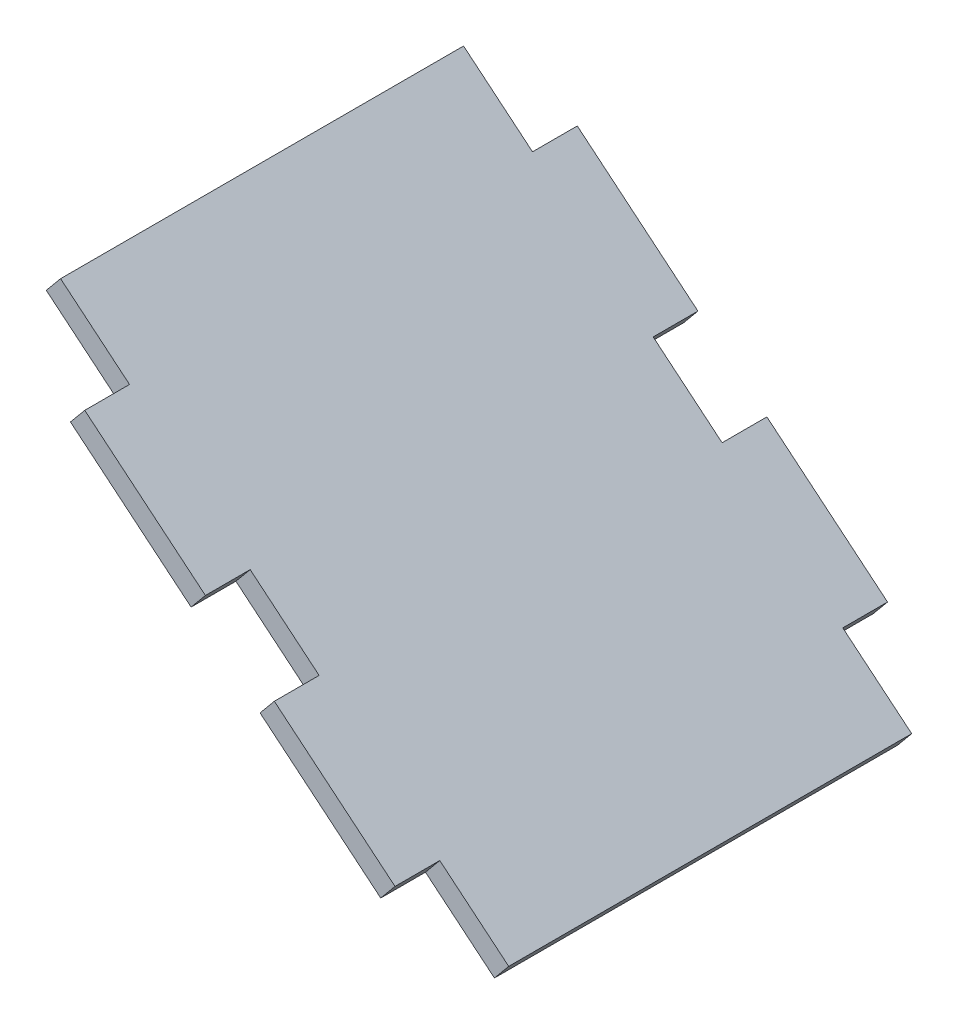
SolidWorks part; units mm, degrees
ref_plane "Front Plane" through (0, 0, 0) normal (0, 0, 1) x (1, 0, 0)
ref_plane "Top Plane" through (0, 0, 0) normal (0, 1, 0) x (1, 0, 0)
ref_plane "Right Plane" through (0, 0, 0) normal (1, 0, 0) x (0, 0, -1)
sketch "Sketch1" plane through (0, 0, 0) normal (0, 0, 1) x (1, 0, 0)
  line L0 (503.9907, 281.5902) -> (440.437, 334.2726)
  line L1 (440.437, 334.2726) -> (442.4633, 336.7169)
  line L2 (442.4633, 336.7169) -> (506.0169, 284.0345)
  line L3 (506.0169, 284.0345) -> (503.9907, 281.5902)
  dimension "D1" = 3.175
  dimension "D2" = 82.55
extrude "Boss-Extrude1" add sketch "Sketch1" against normal blind 69.85 contours L2 L3 L0 L1
sketch "Sketch2" plane through (345.6466, 416.9724, 0) normal (0.6382, 0.7699, 0) x (0.7699, -0.6382, 0)
  line L0 (-39.4351, 63.5) -> (245.6529, 63.5) construction
  line L1 (125.7554, 69.85) -> (138.4554, 69.85)
  line L2 (125.7554, 69.85) -> (125.7554, 63.5)
  line L3 (125.7554, 63.5) -> (138.4554, 63.5)
  line L4 (138.4554, 69.85) -> (138.4554, 63.5)
  line L5 (125.7554, 69.85) -> (208.3054, 69.85) construction
  line L6 (160.6804, 69.85) -> (173.3804, 69.85)
  line L7 (160.6804, 69.85) -> (160.6804, 63.5)
  line L8 (160.6804, 63.5) -> (173.3804, 63.5)
  line L9 (173.3804, 69.85) -> (173.3804, 63.5)
  line L10 (245.6529, 6.35) -> (-39.4351, 6.35) construction
  line L11 (208.3054, 69.85) -> (195.6054, 69.85)
  line L12 (208.3054, 69.85) -> (208.3054, 63.5)
  line L13 (208.3054, 63.5) -> (195.6054, 63.5)
  line L14 (195.6054, 69.85) -> (195.6054, 63.5)
  line L15 (125.7554, 0) -> (138.4554, 0)
  line L16 (125.7554, 0) -> (125.7554, 6.35)
  line L17 (125.7554, 6.35) -> (138.4554, 6.35)
  line L18 (138.4554, 0) -> (138.4554, 6.35)
  line L19 (125.7554, 0) -> (208.3054, 0) construction
  line L20 (160.6804, 0) -> (173.3804, 0)
  line L21 (160.6804, 0) -> (160.6804, 6.35)
  line L22 (160.6804, 6.35) -> (173.3804, 6.35)
  line L23 (173.3804, 0) -> (173.3804, 6.35)
  line L25 (208.3054, 0) -> (195.6054, 0)
  line L26 (208.3054, 0) -> (208.3054, 6.35)
  line L27 (208.3054, 6.35) -> (195.6054, 6.35)
  line L28 (195.6054, 0) -> (195.6054, 6.35)
  dimension "D1" = 12.7
  dimension "D2" = 12.7
  dimension "D3" = 12.7
  dimension "D4" = 22.225
  dimension "D5" = 12.7
  dimension "D6" = 12.7
  dimension "D7" = 12.7
  dimension "D8" = 22.225
extrude "Cut-Extrude1" cut sketch "Sketch2" against normal through all
